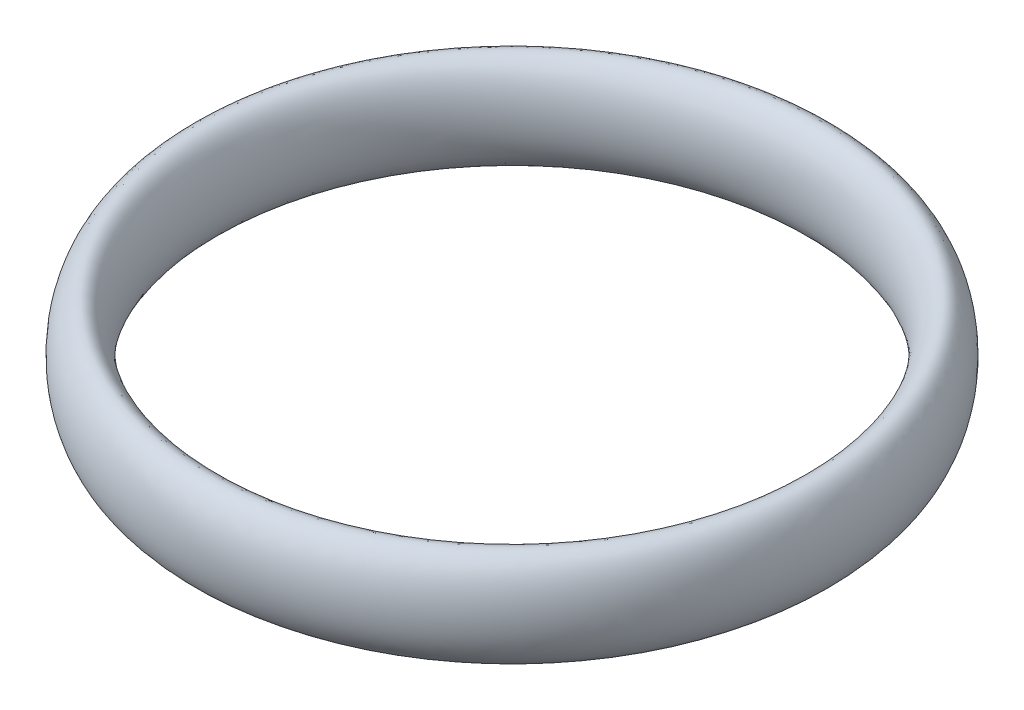
SolidWorks part; units mm, degrees
material "PW20:30:Sc:0:"
ref_plane "Plane1" through (0, 0, 0) normal (0, 0, 1) x (1, 0, 0)
ref_plane "Plane2" through (0, 0, 0) normal (0, 1, 0) x (1, 0, 0)
ref_plane "Plane3" through (0, 0, 0) normal (1, 0, 0) x (0, 0, -1)
sketch "Sketch1" plane through (0, 0, 0) normal (0, 0, 1) x (1, 0, 0)
  line L0 (0, 0) -> (0, 2.032) construction
  line L1 (6.35, 2.032) -> (6.35, 0) construction
  ellipse E0 centre (6.35, 1.016) end of major axis (6.35, 2.032) minor radius 0.508
  dimension "D1" = 2.032
  dimension "D2" = 1.016
  dimension "D3" = 5.842
revolve "Body" add sketch "Sketch1" angle 360 about L0
